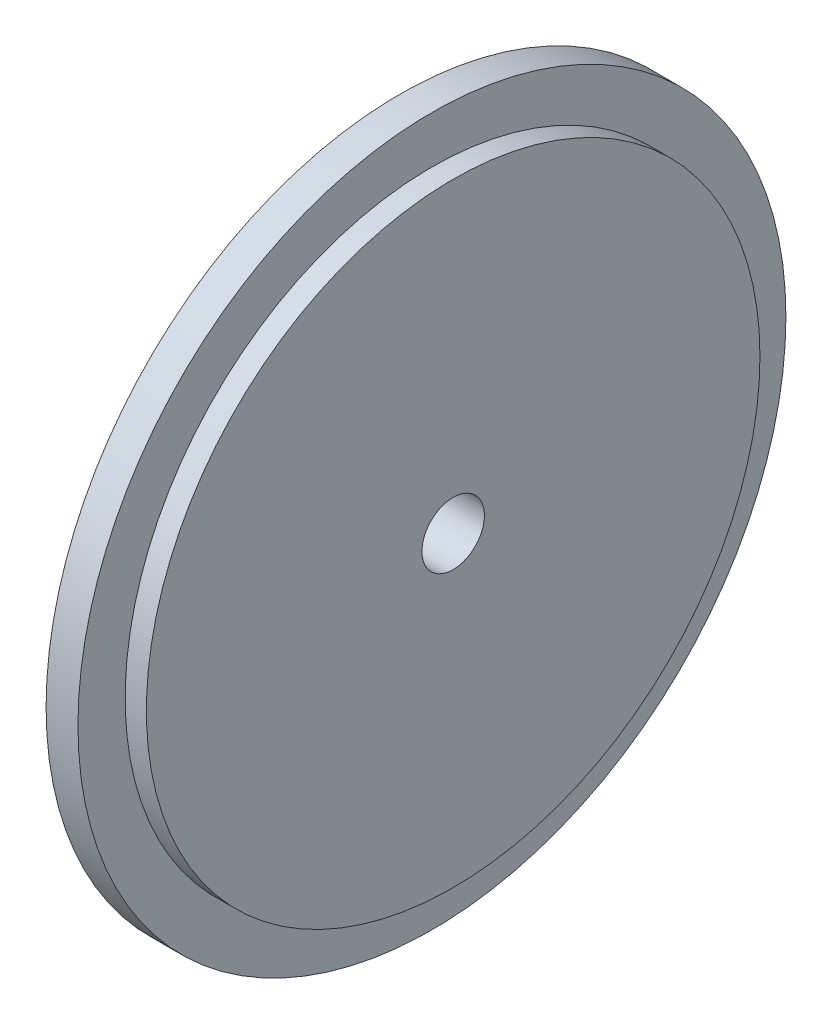
SolidWorks part; units mm, degrees
ref_plane "Front Plane" through (0, 0, 0) normal (0, 0, 1) x (1, 0, 0)
ref_plane "Top Plane" through (0, 0, 0) normal (0, 1, 0) x (1, 0, 0)
ref_plane "Right Plane" through (0, 0, 0) normal (1, 0, 0) x (0, 0, -1)
sketch "Sketch1" plane through (0, 0, 0) normal (1, 0, 0) x (0, 0, -1)
  circle A0 centre (0, 0) radius 30
  circle A1 centre (0, 0) radius 2.65
  dimension "D1" = 60
  dimension "D2" = 5.3
extrude "Boss-Extrude1" add sketch "Sketch1" along normal blind 4.5
sketch "Sketch2" plane through (4.5, 0, 0) normal (1, 0, 0) x (0, 0, -1)
  circle A0 centre (0, 0) radius 26
  circle A2 centre (0, 0) radius 50
  dimension "D1" = 52
  dimension "D2" = 100
extrude "Cut-Extrude1" cut sketch "Sketch2" against normal blind 1.8
